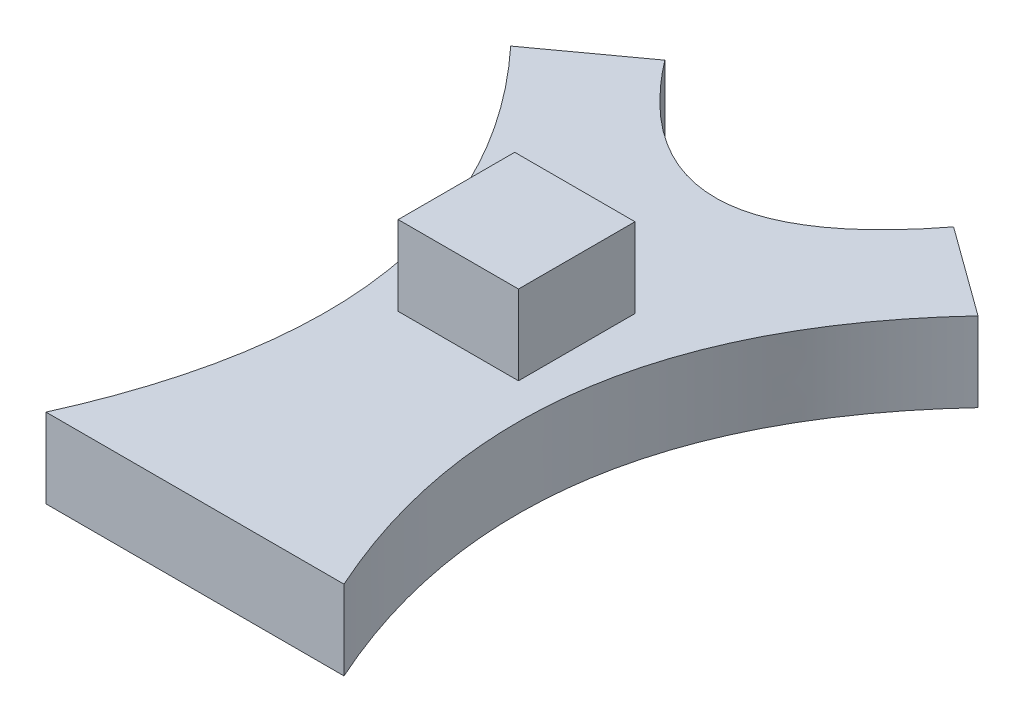
SolidWorks part; units mm, degrees
ref_plane "Front Plane" through (0, 0, 0) normal (0, 0, 1) x (1, 0, 0)
ref_plane "Top Plane" through (0, 0, 0) normal (0, 1, 0) x (1, 0, 0)
ref_plane "Right Plane" through (0, 0, 0) normal (1, 0, 0) x (0, 0, -1)
sketch "Sketch1" plane through (0, 0, 0) normal (0, 1, 0) x (1, 0, 0)
  line L0 (-23.7764, 32.7254) -> (0, 0) construction
  line L1 (0, 50) -> (-47.5528, 15.4508) construction
  line L2 (-47.5528, 15.4508) -> (-29.3893, -40.4508) construction
  line L3 (-29.3893, -40.4508) -> (29.3893, -40.4508) construction
  line L4 (29.3893, -40.4508) -> (47.5528, 15.4508) construction
  line L5 (47.5528, 15.4508) -> (0, 50) construction
  line L6 (0, 0) -> (23.7764, 32.7254) construction
  line L7 (0, 0) -> (0, -40.4508) construction
  line L8 (-42.5325, 0) -> (0, 0) construction
  line L9 (0, 0) -> (42.5325, 0) construction
  line L13 (0, 50) -> (0, 0) construction
  line L14 (0, 0) -> (-38.471, -12.5) construction
  line L15 (-18.7411, -40.4508) -> (18.7411, -40.4508)
  line L16 (-29.3893, 28.6475) -> (-18.1636, 36.8034)
  line L17 (18.1636, 36.8034) -> (29.3893, 28.6475)
  circle A0 centre (0, 0) radius 50 construction
  spline S0 degree 2 poles (-29.3893, 28.6475) (-1.2277, -1.5346) (-18.7411, -40.4508) knots 0 0 0 1 1 1
  spline S1 degree 2 poles (29.3893, 28.6475) (1.2277, -1.5346) (18.7411, -40.4508) knots 0 0 0 1 1 1
  spline S2 degree 2 poles (-18.1636, 36.8034) (0, 13.1966) (18.1636, 36.8034) knots 0 0 0 1 1 1
  point P20 (-18.1636, 36.8034)
  point P21 (18.1636, 36.8034)
  dimension "D1" = 100
extrude "Boss-Extrude1" add sketch "Sketch1" along normal blind 10
sketch "Sketch2" plane through (0, 10, 0) normal (0, 1, 0) x (1, 0, 0)
  line L1 (-7.5653, 7.3289) -> (7.5653, 7.3289)
  line L2 (-7.5653, 7.3289) -> (-7.5653, -7.3289)
  line L3 (-7.5653, -7.3289) -> (7.5653, -7.3289)
  line L4 (7.5653, 7.3289) -> (7.5653, -7.3289)
  line L5 (-7.5653, 7.3289) -> (7.5653, -7.3289) construction
  line L6 (-7.5653, -7.3289) -> (7.5653, 7.3289) construction
  point P0 (0, 0)
extrude "Boss-Extrude4" add sketch "Sketch2" along normal blind 10
equation "\"D1@Sketch1\" = .10"
